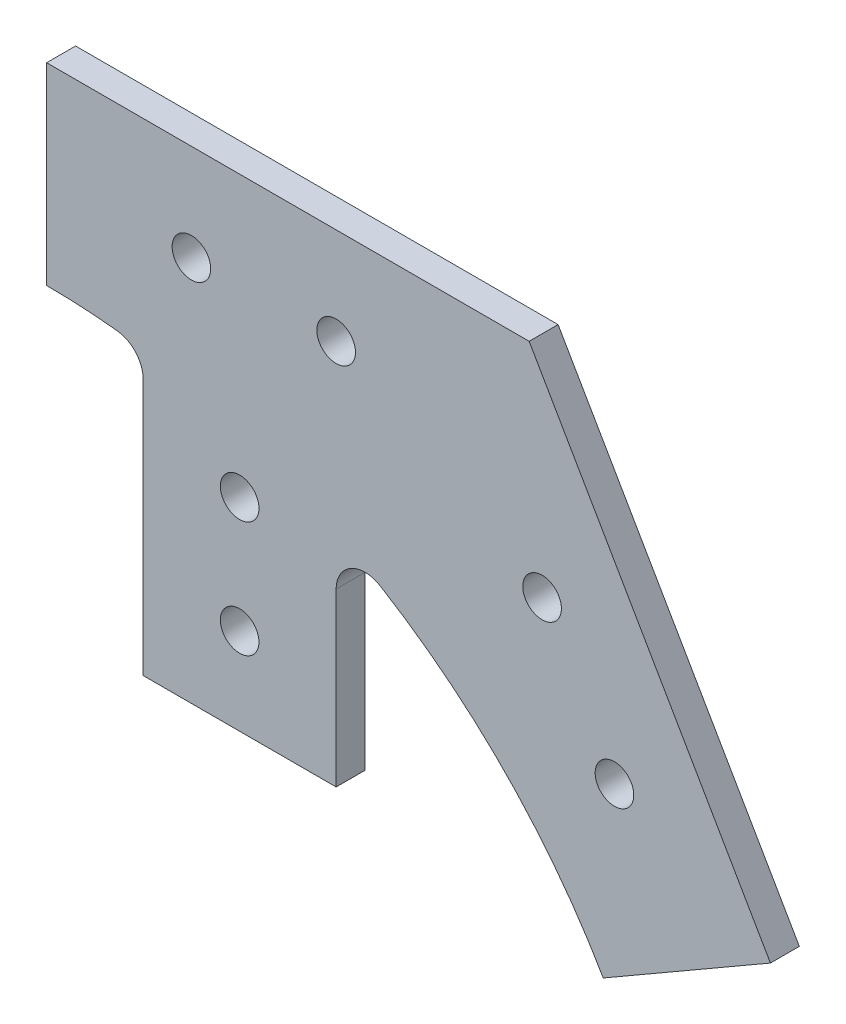
SolidWorks part; units mm, degrees
ref_plane "前视基准面" through (0, 0, 0) normal (0, 0, 1) x (1, 0, 0)
ref_plane "上视基准面" through (0, 0, 0) normal (0, 1, 0) x (1, 0, 0)
ref_plane "右视基准面" through (0, 0, 0) normal (1, 0, 0) x (0, 0, -1)
sketch "草图1" plane through (0, 0, 0) normal (0, 0, 1) x (1, 0, 0)
  line L0 (-22.3244, -1.3531) -> (-22.3244, -27.9667)
  line L1 (-22.3244, -27.9667) -> (-2.3244, -27.9667)
  line L2 (-2.3244, -27.9667) -> (-2.3244, -10.1975)
  line L3 (25.3551, -31.268) -> (42.6756, -21.268)
  line L4 (42.6756, -21.268) -> (17.6756, 22.0333)
  line L5 (17.6756, 22.0333) -> (-32.3244, 22.0333)
  line L6 (-32.3244, 22.0333) -> (-32.3244, 2.0333)
  circle A0 centre (-17.3244, 12.0333) radius 2
  circle A1 centre (-2.3244, 12.0333) radius 2
  circle A2 centre (19.0153, -0.2872) radius 2
  circle A3 centre (26.5153, -13.2776) radius 2
  arc A4 (-24.9943, 1.6287) -> (-32.3244, 2.0333) centre (-32.3244, -64.5693) ccw
  arc A5 (-22.3244, -1.3531) -> (-24.9943, 1.6287) centre (-25.3244, -1.3531) ccw
  arc A6 (2.2321, -7.6329) -> (-2.3244, -10.1975) centre (0.6756, -10.1975) ccw
  arc A7 (25.3551, -31.268) -> (2.2321, -7.6329) centre (-32.3244, -64.5693) ccw
  circle A8 centre (-12.3244, -18.9667) radius 2
  circle A9 centre (-12.3244, -6.9667) radius 2
extrude "凸台-拉伸1" add sketch "草图1" along normal blind 3
